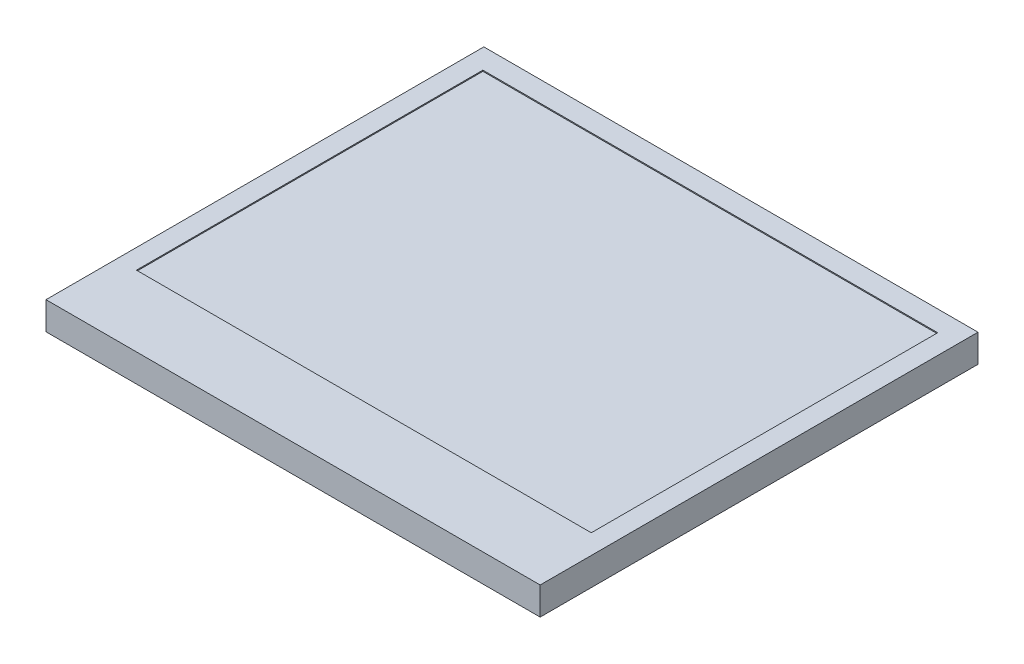
SolidWorks part; units mm, degrees
ref_plane "Front Plane" through (0, 0, 0) normal (0, 0, 1) x (1, 0, 0)
ref_plane "Top Plane" through (0, 0, 0) normal (0, 1, 0) x (1, 0, 0)
ref_plane "Right Plane" through (0, 0, 0) normal (1, 0, 0) x (0, 0, -1)
sketch "Sketch1" plane through (0, 0, 0) normal (0, 1, 0) x (1, 0, 0)
  line L1 (-23.25, -20.6) -> (23.25, -20.6)
  line L2 (-23.25, -20.6) -> (-23.25, 20.6)
  line L3 (-23.25, 20.6) -> (23.25, 20.6)
  line L4 (23.25, -20.6) -> (23.25, 20.6)
  line L5 (-23.25, -20.6) -> (23.25, 20.6) construction
  line L6 (-23.25, 20.6) -> (23.25, -20.6) construction
  point P0 (0, 0)
  dimension "D1" = 46.5
  dimension "D2" = 41.2
extrude "Boss-Extrude1" add sketch "Sketch1" along normal blind 2.62
sketch "Sketch2" plane through (0, 2.62, 0) normal (0, 1, 0) x (1, 0, 0)
  line L0 (23.25, 20.6) -> (-23.25, 20.6) construction
  line L1 (-21.4, 18.66) -> (21.4, 18.66)
  line L2 (-21.4, 18.66) -> (-21.4, -13.94)
  line L3 (-21.4, -13.94) -> (21.4, -13.94)
  line L4 (21.4, 18.66) -> (21.4, -13.94)
  line L5 (0, 20.6) -> (0, -20.6) construction
  line L6 (-23.25, -20.6) -> (23.25, -20.6) construction
  point P10 (0, 18.66)
  dimension "D1" = 42.8
  dimension "D2" = 32.6
  dimension "D3" = 1.94
extrude "Cut-Extrude1" cut sketch "Sketch2" against normal blind 0.1
